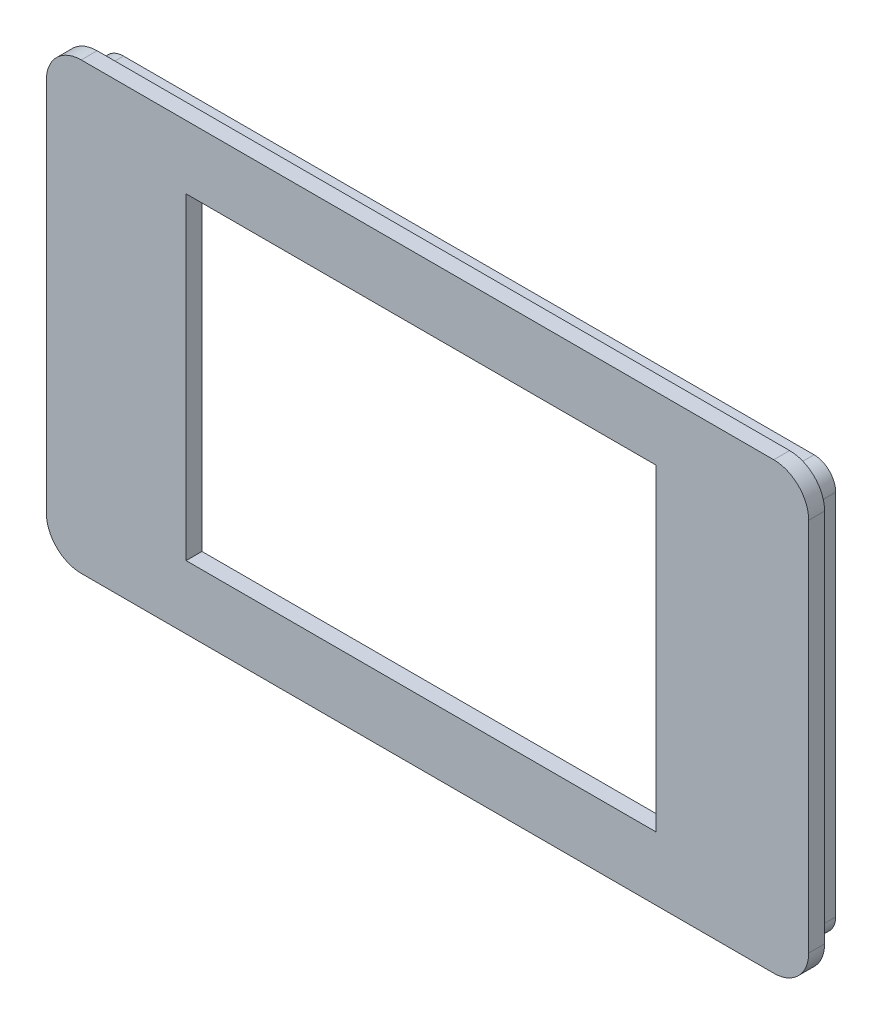
SolidWorks part; units mm, degrees
ref_plane "前视基准面" through (0, 0, 0) normal (0, 0, 1) x (1, 0, 0)
ref_plane "上视基准面" through (0, 0, 0) normal (0, 1, 0) x (1, 0, 0)
ref_plane "右视基准面" through (0, 0, 0) normal (1, 0, 0) x (0, 0, -1)
sketch "草图1" plane through (0, 0, 0) normal (0, 0, 1) x (1, 0, 0)
  line L1 (-51.3287, 35.0683) -> (68.6713, 35.0683)
  line L2 (-51.3287, 35.0683) -> (-51.3287, -34.9317)
  line L3 (-51.3287, -34.9317) -> (68.6713, -34.9317)
  line L4 (68.6713, 35.0683) -> (68.6713, -34.9317)
  line L9 (-29.3287, 25.0683) -> (44.6713, 25.0683)
  line L10 (-29.3287, 25.0683) -> (-29.3287, -24.9317)
  line L11 (-29.3287, -24.9317) -> (44.6713, -24.9317)
  line L12 (44.6713, 25.0683) -> (44.6713, -24.9317)
  line L13 (-29.3287, 25.0683) -> (44.6713, -24.9317) construction
  line L14 (-29.3287, -24.9317) -> (44.6713, 25.0683) construction
  point P4 (7.6713, 0.0683)
  dimension "D1" = 70
  dimension "D2" = 120
  dimension "D3" = 50
  dimension "D4" = 74
  dimension "D5" = 24
  dimension "D6" = 10
extrude "凸台-拉伸1" add sketch "草图1" along normal blind 2.5
sketch "草图2" plane through (0, 0, 0) normal (0, 0, -1) x (-1, 0, 0)
  line L11 (-63.0213, 32.4183) -> (45.6787, 32.4183)
  line L12 (-66.4213, 29.0183) -> (-66.4213, -28.8817)
  line L13 (-63.0213, -32.2817) -> (45.6787, -32.2817)
  line L14 (49.0787, 29.0183) -> (49.0787, -28.8817)
  line L15 (-66.4213, 32.4183) -> (49.0787, -32.2817) construction
  line L16 (-66.4213, -32.2817) -> (49.0787, 32.4183) construction
  arc A0 (45.6787, 32.4183) -> (49.0787, 29.0183) centre (45.6787, 29.0183) cw
  arc A1 (45.6787, -32.2817) -> (49.0787, -28.8817) centre (45.6787, -28.8817) ccw
  arc A2 (-66.4213, -28.8817) -> (-63.0213, -32.2817) centre (-63.0213, -28.8817) ccw
  arc A3 (-63.0213, 32.4183) -> (-66.4213, 29.0183) centre (-63.0213, 29.0183) ccw
  point P0 (-8.6713, 0.0683)
  point P5 (-8.6713, 0.0683)
  dimension "D3" = 3.4
  dimension "D1" = 64.7
  dimension "D2" = 115.5
fillet "圆角1" radius 5.5 4 edges at (-51.3287, 35.0683, 1.25) (-51.3287, -34.9317, 1.25) (68.6713, -34.9317, 1.25) (68.6713, 35.0683, 1.25)
extrude "拉伸-薄壁1" add sketch "草图2" along normal blind 4 thin contours A2 L13 A1 L14 A0 L11 A3 L12
